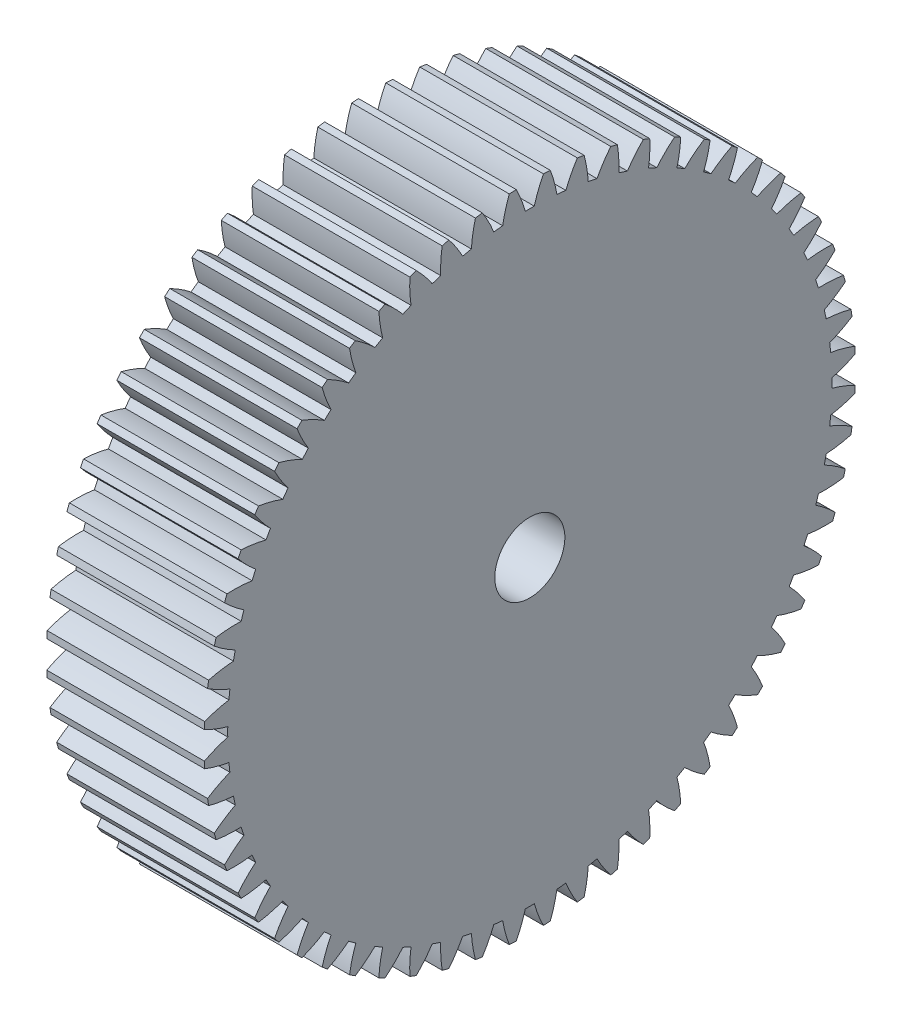
SolidWorks part; units mm, degrees
ref_plane "Plane1" through (0, 0, 0) normal (0, 0, 1) x (1, 0, 0)
ref_plane "Plane2" through (0, 0, 0) normal (0, 1, 0) x (1, 0, 0)
ref_plane "Plane3" through (0, 0, 0) normal (1, 0, 0) x (0, 0, -1)
other "Configuration Table"
sketch "HoldingSke" plane through (0, 0, 0) normal (0, 1, 0) x (1, 0, 0)
  line L0 (0, 0) -> (0.1667, -0.2887)
  line L1 (-15, 0) -> (100, 0) construction
  line L2 (0, 0) -> (-2.1039, 2.3779)
  line L3 (0, 0) -> (-11.863, 4.5341)
  line L4 (0, 0) -> (4.318, 7.479)
  line L5 (0, 0) -> (-46.8476, -17.4728)
  line L6 (0, 0) -> (-37.3033, -25.1687)
  line L7 (-2.1039, 2.3779) -> (8.6586, 51.2059)
  line L8 (-76.2, 54.61) -> (-73.4, 54.61)
  line L9 (-71.009, 38.7566) -> (-53.1078, 45.2721)
  line L10 (-76.2, 71.12) -> (104.1128, 71.12)
  line L11 (0, 0) -> (-45, 0)
  line L12 (-76.2, 101.6) -> (-76.093, 101.6)
  line L13 (24.9733, 27.94) -> (52.9518, 28.4284)
  line L14 (24.9733, 27.94) -> (24.9743, 27.94)
  line L15 (24.9733, 27.94) -> (100.4006, 29.5858)
  line L16 (-63.627, -3) -> (-12.827, -3)
  circle A0 centre (0, 0) radius 10
  circle A1 centre (0, 0) radius 37.5
  circle A2 centre (0, 0) radius 37.5
  circle A3 centre (0, 0) radius 10
  dimension "MHD" = 75
  dimension "Hub_dia" = 75
  dimension "Bore" = 20
  dimension "MBD" = 20
  dimension "Num_teeth" = 60
  dimension "Pitch" = 0.3333
  dimension "Overall_len" = 50
  dimension "Show_teeth" = 60
  dimension "Thickness" = 45
  dimension "OAL" = 50.0001
  dimension "T_dim" = 2.8
  dimension "Ap" = 20
  dimension "H" = 19.05
  dimension "Pitch_radius" = 180.3128
  dimension "Width" = 45
  dimension "Backlash" = 0.107
  dimension "Addendum_fac" = 1
  dimension "Dedendum_fac" = 1.25
  dimension "Clearance_fac" = 0.25
  dimension "Dedendum_add" = 0.001
  dimension "Module" = 3
sketch "BasProSke" plane through (0, 0, 0) normal (0, 1, 0) x (1, 0, 0)
  line L0 (-10, 0) -> (60, 0) construction
  line L1 (0, 0) -> (0, 93)
  line L2 (0, 0) -> (45, 0)
  line L3 (45, 0) -> (45, 93)
  line L4 (45, 93) -> (0, 93)
  dimension "Thickness" = 45
  dimension "Diameter" = 186
revolve "Base-Revolve" add sketch "BasProSke" angle 360 about L0
sketch "TooCutSke" plane through (0, 0, 0) normal (1, 0, 0) x (0, 0, -1)
  line L1 (0, 0) -> (0, 107) construction
  line L2 (0, 0) -> (-2.5432, 89.9641) construction
  line L3 (0, 0) -> (-9.4177, 179.7011) construction
  line L4 (-2.5432, 89.9641) -> (-4.7089, 89.8506) construction
  arc A0 (1.2793, 86.2395) -> (-1.2793, 86.2395) centre (0, 0) ccw
  arc A1 (3.8999, 92.9436) -> (-3.8999, 92.9436) centre (0, 0) ccw
  circle A2 centre (0, 0) radius 90 construction
  circle A3 centre (0, 0) radius 84.5723 construction
  arc A4 (-1.2793, 86.2395) -> (-3.8999, 92.9436) centre (-35.951, 76.5507) ccw
  arc A5 (3.8999, 92.9436) -> (1.2793, 86.2395) centre (35.951, 76.5507) ccw
  dimension "Root_dia" = 172.498
  dimension "Overcut_dia" = 186.0508
  dimension "Pitch_dia" = 180
  dimension "Base_dia" = 169.1447
  dimension "Flank_rad" = 36
  dimension "Half_ang" = 3
  dimension "Half_CT" = 2.1687
extrude "ToothCut" cut sketch "TooCutSke" along normal through all
fillet "Breaks" [suppressed] radius 0.06
fillet "RootFillets" [suppressed] radius 0.751
pattern_circular "TeethCuts" count 60 every 6 about axis through (-10, 0, 0) along (1, 0, 0) of "ToothCut", "RootFillets", "Breaks"
sketch "HubNeaOneSke" plane through (0, 0, 0) normal (-1, 0, 0) x (0, 0, 1)
  circle A0 centre (0, 0) radius 37.5
  dimension "Diameter" = 75
extrude "HubNearOne" [suppressed] add sketch "HubNeaOneSke" along normal blind 5.0001
sketch "HubNeaBotSke" plane through (0, 0, 0) normal (-1, 0, 0) x (0, 0, 1)
  circle A0 centre (0, 0) radius 37.5
  dimension "Diameter" = 75
extrude "HubNearBoth" [suppressed] add sketch "HubNeaBotSke" along normal blind 2.5
ref_plane "FarPln" through (45, 0, 0) normal (1, 0, 0) x (0, 0, -1)
sketch "HubFarSke" plane through (45, 0, 0) normal (1, 0, 0) x (0, 0, -1)
  circle A0 centre (0, 0) radius 37.5
  dimension "Diameter" = 75
extrude "HubFar" [suppressed] add sketch "HubFarSke" along normal blind 2.5
sketch "BorSke" plane through (0, 0, 0) normal (1, 0, 0) x (0, 0, -1)
  circle A0 centre (0, 0) radius 10
  dimension "Diameter" = 20
extrude "Bore" cut sketch "BorSke" along normal mid plane 100.0001
sketch "KeySke" plane through (0, 0, 0) normal (1, 0, 0) x (0, 0, -1)
  line L0 (-3, 0) -> (-3, 12.8)
  line L1 (-3, 12.8) -> (3, 12.8)
  line L2 (3, 12.8) -> (3, 0)
  line L3 (0, 0) -> (0, 34) construction
  line L4 (-3, 0) -> (3, 0)
  dimension "Offset" = 12.8
  dimension "Width" = 6
extrude "Keyway" [suppressed] cut sketch "KeySke" along normal mid plane 100.0001
pattern_circular "Keyway2" [suppressed] count 2 every 90 about axis through (-10, 0, 0) along (1, 0, 0)
equation "' \"Module@HoldingSke\" = 6.35"
equation "' \"Num_teeth@HoldingSke\" = 12"
equation "' \"Ap@HoldingSke\" =  20"
equation "' \"Ap@HoldingSke\" = 20"
equation "' \"Width@HoldingSke\" = 0.5 * 25.4"
equation "' \"Hub_dia@HoldingSke\"= 1 * 25.4"
equation "' \"Hub_dia@HoldingSke\" = 1 * 25.4"
equation "' \"Overall_len@HoldingSke\" = 1.0 * 25.4"
equation "' \"Bore@HoldingSke\" = 0.75 * 25.4"
equation "' \"T_dim@HoldingSke\" = 0.1 * 25.4"
equation "' \"Width@KeySke\" = 0.25 * 25.4"
equation "' \"Show_teeth@HoldingSke\" = 13"
equation "' \"Backlash@HoldingSke\" = 0.009 * 25.4"
equation "' \"Addendum_fac@HoldingSke\" = 1.0"
equation "' \"Dedendum_fac@HoldingSke\" = 1.25"
equation "' \"Dedendum_add@HoldingSke\" = 0.00005 * 25.4"
equation "' \"Clearance_fac@HoldingSke\" = 0.25"
equation "\"Pitch@HoldingSke\" = 1 / \"Module@HoldingSke\""
equation "\"Overcut_dia@TooCutSke\" = (\"Num_teeth@HoldingSke\" + 2 * \"Addendum_fac@HoldingSke\") / \"Pitch@HoldingSke\" + 0.002 * 25.4"
equation "\"Pitch_dia@TooCutSke\" = \"Num_teeth@HoldingSke\" / \"Pitch@HoldingSke\""
equation "\"Base_dia@TooCutSke\" = \"Num_teeth@HoldingSke\" / \"Pitch@HoldingSke\" * cos((\"Ap@HoldingSke\"  * 3.14159265 / 180))"
equation "\"Root_dia@TooCutSke\" = (\"Num_teeth@HoldingSke\" + 2) / \"Pitch@HoldingSke\" - 2 * (\"Addendum_fac@HoldingSke\" + \"Dedendum_fac@HoldingSke\") / \"Pitch@HoldingSke\" - \"Dedendum_add@HoldingSke\" * 2"
equation "\"Half_ang@TooCutSke\" = 180 / \"Num_teeth@HoldingSke\""
equation "\"Half_CT@TooCutSke\" = \"Num_teeth@HoldingSke\" / \"Pitch@HoldingSke\" * sin((3.14159265 / 2 / \"Num_teeth@HoldingSke\")) / 2 - 7 * \"Backlash@HoldingSke\" / 4"
equation "\"Flank_rad@TooCutSke\" = \"Num_teeth@HoldingSke\" / \"Pitch@HoldingSke\" / 5"
equation "\"Radius@RootFillets\" = \"Clearance_fac@HoldingSke\" / \"Pitch@HoldingSke\" + \"Dedendum_add@HoldingSke\""
equation "\"Break_rad@Breaks\" = 0.02 / \"Pitch@HoldingSke\""
equation "\"Thickness@HoldingSke\" = \"Width@HoldingSke\""
equation "\"OAL@HoldingSke\" = \"Thickness@HoldingSke\""
equation "\"MHD@HoldingSke\" = (\"Num_teeth@HoldingSke\" + 2) / \"Pitch@HoldingSke\" - 2 * (\"Addendum_fac@HoldingSke\" + \"Dedendum_fac@HoldingSke\")  / \"Pitch@HoldingSke\" - \"Dedendum_add@HoldingSke\" * 2"
equation "\"MBD@HoldingSke\" = (\"Num_teeth@HoldingSke\" + 2) / \"Pitch@HoldingSke\" - 2 * (\"Addendum_fac@HoldingSke\" + \"Dedendum_fac@HoldingSke\")  / \"Pitch@HoldingSke\" - \"Dedendum_add@HoldingSke\" * 2 - 0.002 * 25.4"
equation "\"MHD@HoldingSke\" = ((sgn( \"MHD@HoldingSke\" - \"Hub_dia@HoldingSke\" )-1)*( \"MHD@HoldingSke\" - \"Hub_dia@HoldingSke\" ))/-2+ \"Hub_dia@HoldingSke\""
equation "\"MBD@HoldingSke\" = ((sgn( \"MBD@HoldingSke\" - \"Bore@HoldingSke\" )-1)*( \"MBD@HoldingSke\" - \"Bore@HoldingSke\" ))/-2+ \"Bore@HoldingSke\""
equation "\"OAL@HoldingSke\" = ((sgn( \"OAL@HoldingSke\" - \"Overall_len@HoldingSke\" )+1)*( \"OAL@HoldingSke\" - \"Overall_len@HoldingSke\" ))/2 + \"Overall_len@HoldingSke\" + 0.000002 * 25.4"
equation "\"Num_teeth@TeethCuts\" = int( \"Show_teeth@HoldingSke\" ) + 1"
equation "\"Num_teeth@TeethCuts\" = ((sgn( \"Num_teeth@TeethCuts\" - \"Num_teeth@HoldingSke\" )-1)*( \"Num_teeth@TeethCuts\" - \"Num_teeth@HoldingSke\" ))/-2+ \"Num_teeth@HoldingSke\""
equation "\"Num_teeth@TeethCuts\" = ((sgn( \"Num_teeth@TeethCuts\" - 2.0)+1)*( \"Num_teeth@TeethCuts\" - 2.0))/2 +2.0"
equation "\"Angle@TeethCuts\" = 360.0 / \"Num_teeth@HoldingSke\""
equation "\"Diameter@BasProSke\" = (\"Num_teeth@HoldingSke\" + 2 * \"Addendum_fac@HoldingSke\") / \"Pitch@HoldingSke\""
equation "\"Thickness@BasProSke\"  = \"Thickness@HoldingSke\""
equation "' \"Fillet_rad@BasProSke\" =  \"Thickness@HoldingSke\" * 0.05"
equation "' \"Fillet_rad@BasProSke\" = \"Thickness@HoldingSke\" * 0.05"
equation "\"MHD@HoldingSke\" = ((sgn( \"MHD@HoldingSke\" - \"Root_dia@TooCutSke\" )-1)*( \"MHD@HoldingSke\" - \"Root_dia@TooCutSke\" ))/-2+ \"Root_dia@TooCutSke\""
equation "\"Diameter@HubNeaOneSke\" = \"MHD@HoldingSke\""
equation "\"Length@HubNearOne\" = \"OAL@HoldingSke\" - \"Thickness@BasProSke\""
equation "\"Diameter@HubNeaBotSke\" = \"MHD@HoldingSke\""
equation "\"Length@HubNearBoth\" = ( \"OAL@HoldingSke\" - \"Thickness@BasProSke\" ) / 2.0"
equation "\"Thickness@FarPln\" = \"Thickness@BasProSke\""
equation "\"Diameter@HubFarSke\" = \"MHD@HoldingSke\""
equation "\"Length@HubFar\" = ( \"OAL@HoldingSke\" - \"Thickness@BasProSke\" ) / 2.0"
equation "\"Diameter@BorSke\" = \"MBD@HoldingSke\""
equation "\"D1@Bore\" = \"OAL@HoldingSke\" * 2.0"
equation "\"D1@Keyway\" = \"OAL@HoldingSke\" * 2.0"
equation "\"Offset@KeySke\" = \"T_dim@HoldingSke\" + \"MBD@HoldingSke\" / 2.0"
